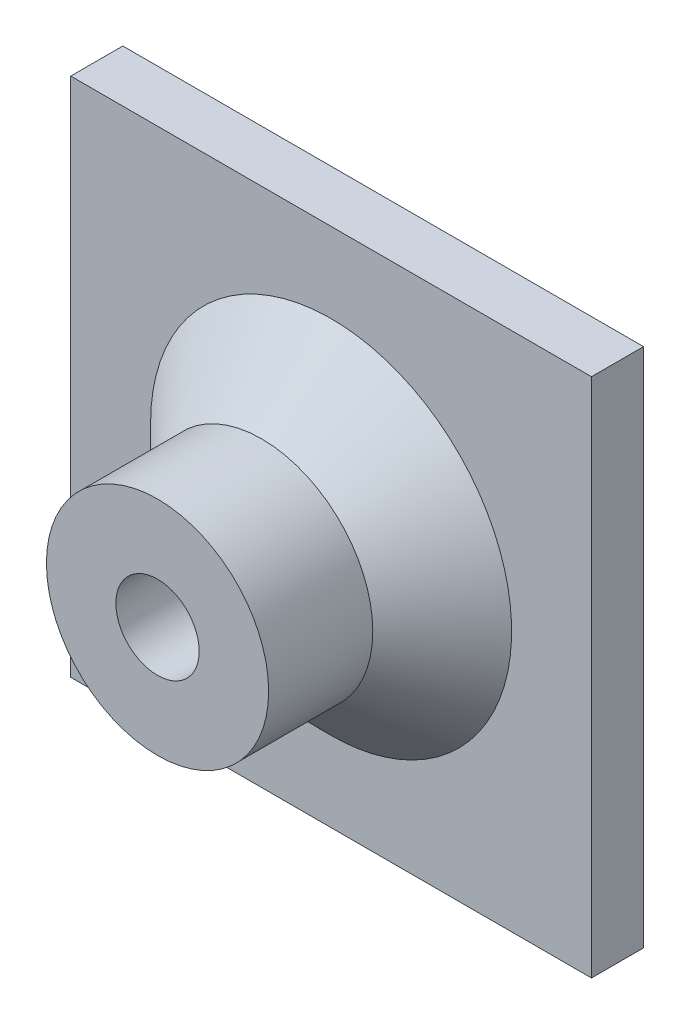
SolidWorks part; units mm, degrees
material "Сосна"
ref_plane "Front" through (0, 0, 0) normal (0, 0, 1) x (1, 0, 0)
ref_plane "Top" through (0, 0, 0) normal (0, 1, 0) x (1, 0, 0)
ref_plane "Right" through (0, 0, 0) normal (1, 0, 0) x (0, 0, -1)
sketch "Эскиз2" plane through (0, 0, 0) normal (0, 0, 1) x (1, 0, 0)
  line L1 (-7.5, -7.5) -> (7.5, -7.5)
  line L2 (-7.5, -7.5) -> (-7.5, 7.5)
  line L3 (-7.5, 7.5) -> (7.5, 7.5)
  line L4 (7.5, -7.5) -> (7.5, 7.5)
  line L5 (-7.5, -7.5) -> (7.5, 7.5) construction
  line L6 (-7.5, 7.5) -> (7.5, -7.5) construction
  circle A0 centre (0, 0) radius 1.2
  point P0 (0, 0)
  dimension "D2" = 2.4
  dimension "D1" = 15
extrude "Основание" add sketch "Эскиз2" along normal blind 1.5
sketch "Эскиз3" plane through (0, 0, 1.5) normal (0, 0, 1) x (1, 0, 0)
  circle A0 centre (0, 0) radius 3.2
  circle A3 centre (0, 0) radius 1.2
  circle A4 centre (0, 0) radius 1.2 construction
  dimension "D1" = 2
  dimension "D2" = 2
extrude "Стойка" add sketch "Эскиз3" along normal blind 5
chamfer "Фаска1" distance 1.2 angle 45 1 edges at (1.2, 0, 0)
chamfer "Фаска2" distance 2 angle 45 1 edges at (-3.2, 0, 1.5)
